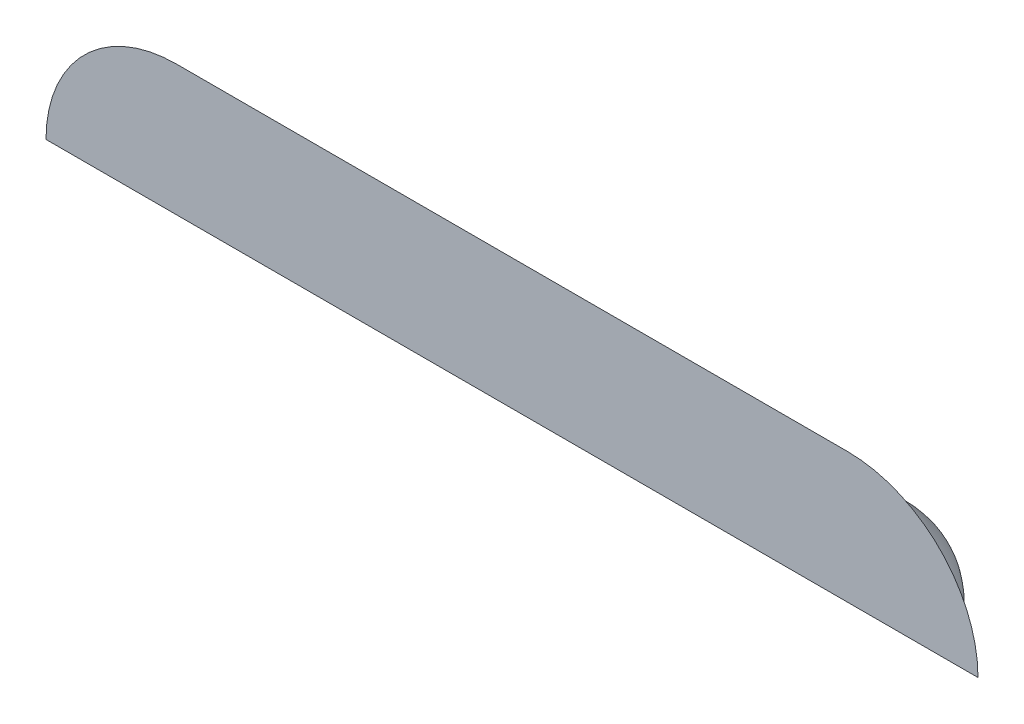
SolidWorks part; units mm, degrees
ref_plane "Front Plane" through (0, 0, 0) normal (0, 0, 1) x (1, 0, 0)
ref_plane "Top Plane" through (0, 0, 0) normal (0, 1, 0) x (1, 0, 0)
ref_plane "Right Plane" through (0, 0, 0) normal (1, 0, 0) x (0, 0, -1)
sketch "Sketch1" plane through (0, 0, 0) normal (0, 0, 1) x (1, 0, 0)
  line L1 (-144.5783, 74.5482) -> (5.4217, 74.5482)
  line L2 (-144.5783, 74.5482) -> (-144.5783, -75.4518)
  line L3 (-144.5783, -75.4518) -> (5.4217, -75.4518)
  line L4 (5.4217, 74.5482) -> (5.4217, -75.4518)
  dimension "D1" = 150
  dimension "D2" = 150
extrude "Boss-Extrude1" add sketch "Sketch1" along normal blind 10
sketch "Sketch3" plane through (-144.5783, 0, 0) normal (-1, 0, 0) x (0, 0, 1)
  line L0 (0, 8) -> (0, 0)
  line L1 (0, 74.5482) -> (0, -75.4518) construction
  line L2 (0, 0) -> (-8, 0)
  arc A0 (-8, 0) -> (0, 8) centre (0, 0) cw
  dimension "D1" = 8
  dimension "D2" = 8
extrude "Boss-Extrude2" add sketch "Sketch3" against normal blind 65 from offset 30 offset against normal yes
sketch "Sketch10" plane through (-114.5783, 0, 0) normal (-1, 0, 0) x (0, 0, 1)
  line L2 (-8, 0) -> (0, 0)
  line L3 (0, 0) -> (0, 8)
  line L4 (-8, 0) -> (0, 0)
  line L5 (0, 0) -> (0, 8)
  arc A1 (0, 8) -> (-8, 0) centre (0, 0) ccw
  arc A2 (0, 8) -> (-8, 0) centre (0, 0) ccw
  dimension "D1" = 0
revolve "Revolve2" add sketch "Sketch10" angle 90 about L4
sketch "Sketch11" plane through (-49.5783, 0, 0) normal (1, 0, 0) x (0, 0, -1)
  line L2 (0, 8) -> (0, 0)
  line L3 (0, 0) -> (8, 0)
  line L4 (0, 8) -> (0, 0)
  line L5 (0, 0) -> (8, 0)
  arc A1 (8, 0) -> (0, 8) centre (0, 0) ccw
  arc A2 (8, 0) -> (0, 8) centre (0, 0) ccw
  dimension "D1" = 0
revolve "Revolve3" add sketch "Sketch11" angle 90 about L5
fillet "Fillet1" radius 6 3 edges at (-43.9215, 5.6569, 0) (-120.2352, 5.6569, 0) (-82.0783, 8, 0)
sketch "Sketch12" plane through (0, -75.4518, 0) normal (0, -1, 0) x (1, 0, 0)
  line L4 (-144.5783, 0) -> (5.4217, 0)
  line L5 (5.4217, 0) -> (5.4217, 10)
  line L6 (5.4217, 10) -> (-144.5783, 10)
  line L7 (-144.5783, 10) -> (-144.5783, 0)
  line L8 (-144.5783, 0) -> (5.4217, 0)
  line L9 (5.4217, 0) -> (5.4217, 10)
  line L10 (5.4217, 10) -> (-144.5783, 10)
  line L11 (-144.5783, 10) -> (-144.5783, 0)
  dimension "D1" = 0
extrude "Cut-Extrude1" cut sketch "Sketch12" against normal through all
sketch "Orientation Sketch" plane through (0, 0, 0) normal (0, 0, 1) x (1, 0, 0)
  line L0 (-36.9292, 0) -> (-127.2274, 0) construction
  line L1 (-49.5783, 12.6491) -> (-114.5783, 12.6491) construction
  line L2 (-36.9292, 0) -> (-127.2274, 0)
  line L3 (-49.5783, 12.6491) -> (-114.5783, 12.6491)
  arc A0 (-36.9292, 0) -> (-49.5783, 12.6491) centre (-49.5783, 0) ccw construction
  arc A1 (-114.5783, 12.6491) -> (-127.2274, 0) centre (-114.5783, 0) ccw construction
  arc A2 (-36.9292, 0) -> (-49.5783, 12.6491) centre (-49.5783, 0) ccw
  arc A3 (-114.5783, 12.6491) -> (-127.2274, 0) centre (-114.5783, 0) ccw
  point P3 (-82.0783, 6.3246)
other "FormTool1"
